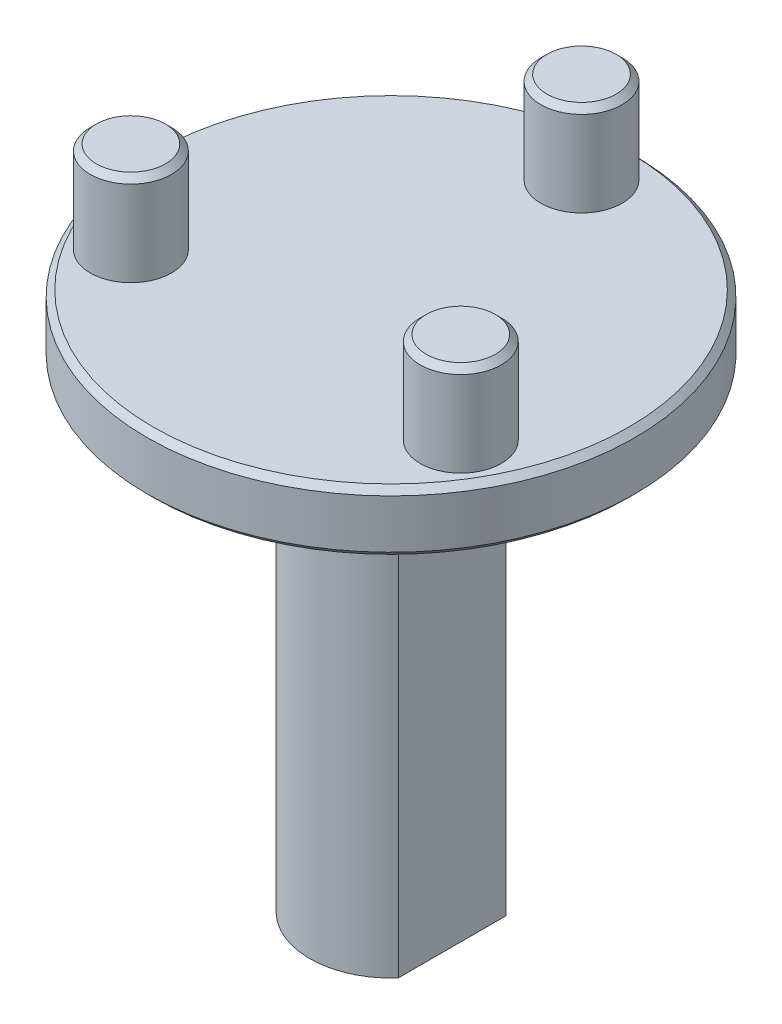
SolidWorks part; units mm, degrees
ref_plane "Front Plane" through (0, 0, 0) normal (0, 0, 1) x (1, 0, 0)
ref_plane "Top Plane" through (0, 0, 0) normal (0, 1, 0) x (1, 0, 0)
ref_plane "Right Plane" through (0, 0, 0) normal (1, 0, 0) x (0, 0, -1)
sketch "Sketch1" plane through (0, 0, 0) normal (0, 1, 0) x (1, 0, 0)
  circle A0 centre (0, 0) radius 12
  dimension "D1" = 24
extrude "Boss-Extrude1" add sketch "Sketch1" along normal blind 3
sketch "Sketch2" plane through (0, 3, 0) normal (0, 1, 0) x (1, 0, 0)
  line L0 (0, 9.37) -> (0, 0) construction
  line L1 (0, 0) -> (-8.1147, -4.685) construction
  line L2 (0, 0) -> (8.1147, -4.685) construction
  circle A0 centre (0, 9.37) radius 2
  circle A1 centre (-8.1147, -4.685) radius 2
  circle A2 centre (8.1147, -4.685) radius 2
  dimension "D4" = 4
  dimension "D5" = 4
  dimension "D6" = 4
  dimension "D1" = 120
  dimension "D2" = 120
  dimension "D3" = 9.37
extrude "Boss-Extrude2" add sketch "Sketch2" along normal blind 4.5
sketch "Sketch3" plane through (0, 0, 0) normal (0, -1, 0) x (1, 0, 0)
  circle A0 centre (0, 0) radius 5
  dimension "D1" = 10
extrude "Boss-Extrude3" add sketch "Sketch3" along normal blind 1
sketch "Sketch4" plane through (0, -1, 0) normal (0, -1, 0) x (1, 0, 0)
  line L0 (-4, 0) -> (3, 0) construction
  line L1 (3, 2.6458) -> (3, -2.6458)
  arc A0 (3, 2.6458) -> (3, -2.6458) centre (0, 0) ccw
  dimension "D1" = 8
  dimension "D2" = 7
extrude "Boss-Extrude4" add sketch "Sketch4" along normal blind 22.5
chamfer "Chamfer1" distance 0.3 angle 45 5 edges at (-8.1147, 7.5, 6.685) (0, 0, 12) (0, 3, 12) (0, 7.5, -7.37) (8.1147, 7.5, 6.685)
